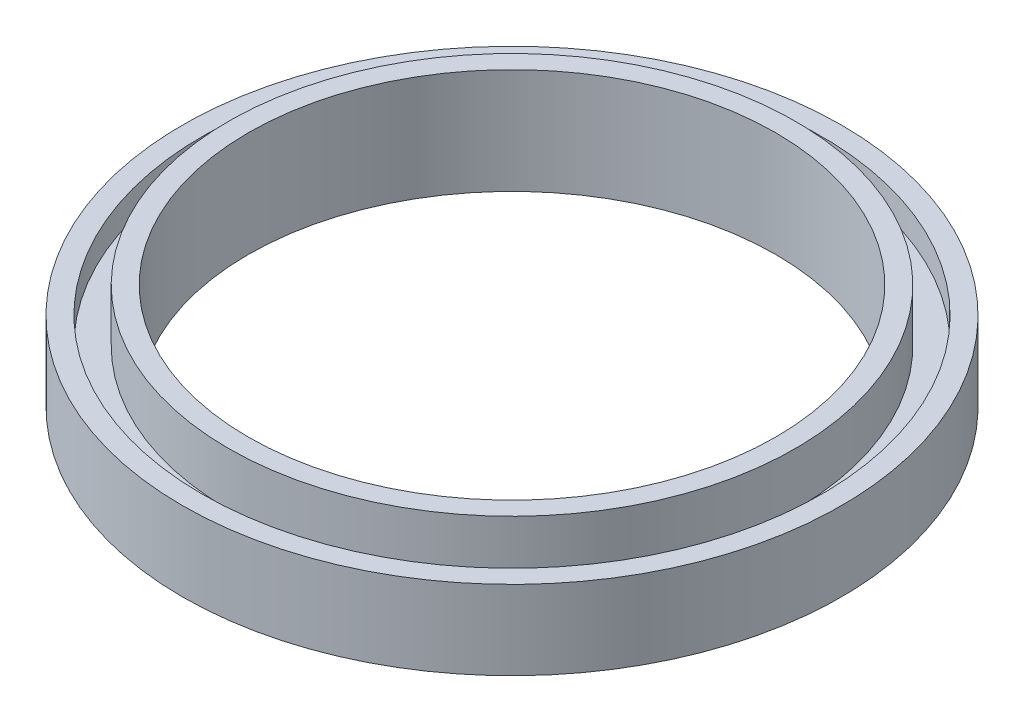
SolidWorks part; units mm, degrees
ref_plane "Front Plane" through (0, 0, 0) normal (0, 0, 1) x (1, 0, 0)
ref_plane "Top Plane" through (0, 0, 0) normal (0, 1, 0) x (1, 0, 0)
ref_plane "Right Plane" through (0, 0, 0) normal (1, 0, 0) x (0, 0, -1)
sketch "Sketch1" plane through (0, 0, 0) normal (0, 1, 0) x (1, 0, 0)
  circle A0 centre (0, 0) radius 25
  dimension "D1" = 50
extrude "Boss-Extrude1" add sketch "Sketch1" along normal blind 8
sketch "Sketch2" plane through (0, 8, 0) normal (0, 1, 0) x (1, 0, 0)
  circle A0 centre (0, 0) radius 23.5
  circle A1 centre (0, 0) radius 21.5
  dimension "D1" = 47
  dimension "D2" = 43
extrude "Cut-Extrude1" cut sketch "Sketch2" against normal blind 4
sketch "Sketch3" plane through (0, 8, 0) normal (0, 1, 0) x (1, 0, 0)
  circle A0 centre (0, 0) radius 25
  circle A1 centre (0, 0) radius 23.5
  dimension "D1" = 50
  dimension "D2" = 47
extrude "Cut-Extrude2" cut sketch "Sketch3" against normal blind 2
sketch "Sketch4" plane through (0, 8, 0) normal (0, 1, 0) x (1, 0, 0)
  circle A0 centre (0, 0) radius 20
  dimension "D1" = 40
extrude "Cut-Extrude3" cut sketch "Sketch4" against normal up to next
